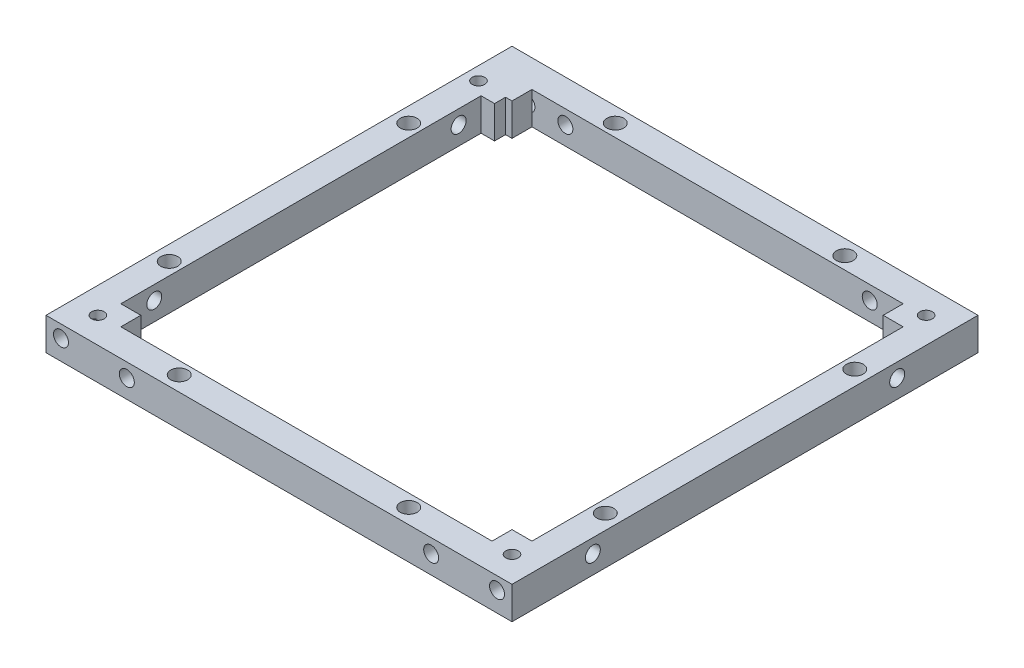
SolidWorks part; units mm, degrees
material "Aluminum"
ref_plane "Front Plane" through (0, 0, 0) normal (0, 0, 1) x (1, 0, 0)
ref_plane "Top Plane" through (0, 0, 0) normal (0, 1, 0) x (1, 0, 0)
ref_plane "Right Plane" through (0, 0, 0) normal (1, 0, 0) x (0, 0, -1)
sketch "Sketch1" plane through (0, 0, 0) normal (0, 1, 0) x (1, 0, 0)
  line L1 (46.7, -46.7) -> (-46.7, -46.7)
  line L2 (46.7, -46.7) -> (46.7, 46.7)
  line L3 (46.7, 46.7) -> (-46.7, 46.7)
  line L4 (-46.7, -46.7) -> (-46.7, 46.7)
  line L5 (46.7, -46.7) -> (-46.7, 46.7) construction
  line L6 (46.7, 46.7) -> (-46.7, -46.7) construction
  line L7 (38.7, -38.7) -> (-38.7, -38.7)
  line L8 (38.7, -38.7) -> (38.7, 38.7)
  line L9 (38.7, 38.7) -> (-38.7, 38.7)
  line L10 (-38.7, -38.7) -> (-38.7, 38.7)
  line L11 (38.7, -38.7) -> (-38.7, 38.7) construction
  line L12 (38.7, 38.7) -> (-38.7, -38.7) construction
  point P0 (0, 0)
  point P6 (0, 0)
  dimension "D1" = 93.4
  dimension "D2" = 93.4
  dimension "D3" = 8
extrude "Boss-Extrude1" add sketch "Sketch1" along normal blind 8
hole_wizard "Ø3.0 (3) Diameter Hole6" positions "Sketch8" profile "Sketch7" hole size "Ø3.0" standard "ANSI Metric"
sketch "Sketch8" plane through (0, 0, 46.7) normal (0, 0, 1) x (1, 0, 0)
  line L0 (46.7, 8) -> (46.7, 0) construction
  line L1 (-46.7, 8) -> (-46.7, 0) construction
  line L2 (-46.7, 0) -> (46.7, 0) construction
  point P0 (43.7, 4)
  point P2 (-43.7, 4)
  dimension "D1" = 3
  dimension "D2" = 3
  dimension "D3" = 4
  dimension "D4" = 4
sketch "Sketch7" plane through (43.7, 4, 46.7) normal (1, 0, 0) x (0, -1, 0)
  line L0 (0, 0) -> (0, 7.5)
  line L1 (0, 7.5) -> (1.5, 7.5)
  line L2 (1.5, 7.5) -> (1.5, 0)
  line L5 (1.5, 0) -> (0, 0)
  line L10 (0, 7.5) -> (-1.5, 7.5) construction
  line L11 (0, -6.35) -> (0, 107.95) construction
  dimension "Hole Dia." = 3
  dimension "Hole Depth" = 7.5
  dimension "Drill Angle" = 180
hole_wizard "Ø3.0 (3) Diameter Hole3" positions "Sketch10" profile "Sketch9" hole size "Ø3.0" standard "ANSI Metric"
sketch "Sketch10" plane through (0, 0, -46.7) normal (0, 0, -1) x (-1, 0, 0)
  line L0 (-46.7, 8) -> (-46.7, 0) construction
  line L1 (46.7, 8) -> (46.7, 0) construction
  line L2 (-46.7, 0) -> (46.7, 0) construction
  point P0 (-43.7, 4)
  point P2 (43.7, 4)
  dimension "D1" = 3
  dimension "D2" = 3
  dimension "D3" = 4
  dimension "D4" = 4
sketch "Sketch9" plane through (43.7, 4, -46.7) normal (1, 0, 0) x (0, 1, 0)
  line L0 (0, 0) -> (0, 7.5)
  line L1 (0, 7.5) -> (1.5, 7.5)
  line L2 (1.5, 7.5) -> (1.5, 0)
  line L5 (1.5, 0) -> (0, 0)
  line L10 (0, 7.5) -> (-1.5, 7.5) construction
  line L11 (0, -6.35) -> (0, 107.95) construction
  dimension "Hole Dia." = 3
  dimension "Hole Depth" = 7.5
  dimension "Drill Angle" = 180
sketch "Sketch27" plane through (0, 8, 0) normal (0, 1, 0) x (1, 0, 0)
  line L0 (-38.7, 38.7) -> (-38.7, -38.7) construction
  line L1 (39.7, -39.7) -> (-39.7, -39.7)
  line L2 (39.7, -39.7) -> (39.7, 39.7)
  line L3 (39.7, 39.7) -> (-39.7, 39.7)
  line L4 (-39.7, -39.7) -> (-39.7, 39.7)
  line L5 (39.7, -39.7) -> (-39.7, 39.7) construction
  line L6 (39.7, 39.7) -> (-39.7, -39.7) construction
  line L7 (38.7, 38.7) -> (-38.7, 38.7) construction
  point P0 (0, 0)
  dimension "D1" = 1
  dimension "D2" = 1
extrude "Cut-Extrude2" cut sketch "Sketch27" against normal blind 10
hole_wizard "Ø3.4 (3.4) Diameter Hole1" positions "Sketch37" profile "Sketch36" hole size "Ø3.4" standard "ANSI Metric" end condition through all
sketch "Sketch37" plane through (0, 0, 0) normal (0, -1, 0) x (-1, 0, 0)
  line L0 (39.7, -39.7) -> (-39.7, -39.7) construction
  line L1 (39.7, 39.7) -> (39.7, -39.7) construction
  line L2 (-39.7, -39.7) -> (-39.7, 39.7) construction
  line L3 (-39.7, 39.7) -> (39.7, 39.7) construction
  point P0 (-23, 43.7)
  point P2 (23, 43.7)
  point P4 (43.7, 23)
  point P6 (43.7, -25)
  point P8 (23, -43.7)
  point P10 (-23, -43.7)
  point P12 (-43.7, -25)
  point P14 (-43.7, 25)
  dimension "D1" = 46
  dimension "D2" = 4
  dimension "D3" = 48
  dimension "D4" = 50
  dimension "D5" = 46
  dimension "D6" = 4
  dimension "D7" = 4
  dimension "D8" = 4
sketch "Sketch36" plane through (23, 0, -43.7) normal (1, 0, 0) x (0, 0, -1)
  line L0 (0, 0) -> (0, 8)
  line L1 (0, 8) -> (1.7, 8)
  line L2 (1.7, 8) -> (1.7, 0)
  line L5 (1.7, 0) -> (0, 0)
  line L11 (0, -6.35) -> (0, 107.95) construction
  dimension "Thru Hole Dia." = 3.4
  dimension "Thru Hole Depth" = 8
sketch "Sketch38" plane through (0, 8, 0) normal (0, 1, 0) x (1, 0, 0)
  line L0 (46.7, 46.7) -> (-46.7, 46.7) construction
  line L1 (41.2, -41.2) -> (-41.2, -41.2)
  line L2 (41.2, -41.2) -> (41.2, 41.2)
  line L3 (41.2, 41.2) -> (-41.2, 41.2)
  line L4 (-41.2, -41.2) -> (-41.2, 41.2)
  line L5 (41.2, -41.2) -> (-41.2, 41.2) construction
  line L6 (41.2, 41.2) -> (-41.2, -41.2) construction
  line L7 (-46.7, 46.7) -> (-46.7, -46.7) construction
  point P0 (0, 0)
  dimension "D1" = 5.5
  dimension "D2" = 5.5
extrude "Cut-Extrude4" cut sketch "Sketch38" against normal blind 10
sketch "Sketch44" plane through (0, 0, 0) normal (0, -1, 0) x (1, 0, 0)
  line L0 (41.2, -41.2) -> (-41.2, -41.2) construction
  line L1 (41.2, -41.2) -> (37.2, -41.2)
  line L2 (41.2, -41.2) -> (41.2, -37.2)
  line L3 (41.2, -37.2) -> (37.2, -37.2)
  line L4 (37.2, -41.2) -> (37.2, -37.2)
  line L5 (41.2, 41.2) -> (41.2, -41.2) construction
  line L6 (0, 0) -> (0, -67.1068) construction
  line L7 (0, 0) -> (66.4168, 0) construction
  line L8 (-37.2, -41.2) -> (-37.2, -37.2)
  line L9 (-41.2, -37.2) -> (-37.2, -37.2)
  line L10 (-41.2, -41.2) -> (-41.2, -37.2)
  line L11 (-41.2, -41.2) -> (-37.2, -41.2)
  line L12 (-41.2, 41.2) -> (-37.2, 41.2)
  line L13 (-41.2, 41.2) -> (-41.2, 37.2)
  line L14 (-41.2, 37.2) -> (-37.2, 37.2)
  line L15 (-37.2, 41.2) -> (-37.2, 37.2)
  line L16 (37.2, 41.2) -> (37.2, 37.2)
  line L17 (41.2, 37.2) -> (37.2, 37.2)
  line L18 (41.2, 41.2) -> (41.2, 37.2)
  line L19 (41.2, 41.2) -> (37.2, 41.2)
  dimension "D1" = 4
  dimension "D2" = 4
extrude "Boss-Extrude2" add sketch "Sketch44" against normal blind 8
sketch "Sketch45" plane through (0, 8, 0) normal (0, 1, 0) x (1, 0, 0)
  line L1 (-42.5, 38.5) -> (-38.5, 38.5)
  line L2 (-42.5, 38.5) -> (-42.5, 35)
  line L3 (-42.5, 35) -> (-38.5, 35)
  line L4 (-38.5, 38.5) -> (-38.5, 35)
  dimension "D1" = 4
  dimension "D2" = 3.5
extrude "Boss-Extrude3" add sketch "Sketch45" against normal blind 8
hole_wizard "Tap Drill for M3x0.5 Tap1" positions "Sketch48" profile "Sketch46" hole size "M3x0.5" standard "ANSI Metric" end condition through all
sketch "Sketch48" plane through (0, 8, 0) normal (0, 1, 0) x (1, 0, 0)
  point P0 (41.5, 41.5)
  point P2 (41.5, -41.5)
  point P4 (-41.5, -41.5)
  point P6 (-44.05, 37.33)
sketch "Sketch46" plane through (41.5, 8, -41.5) normal (1, 0, 0) x (0, 0, 1)
  line L0 (0, 0) -> (0, 8)
  line L1 (0, 8) -> (1.25, 8)
  line L2 (1.25, 8) -> (1.25, 0)
  line L5 (1.25, 0) -> (0, 0)
  line L11 (0, -6.35) -> (0, 107.95) construction
  dimension "Thru Hole Dia." = 2.5
  dimension "Thru Hole Depth" = 8
sketch "Sketch49" plane through (46.7, 0, 0) normal (1, 0, 0) x (0, 0, -1)
  line L0 (46.7, 8) -> (46.7, 0) construction
  line L1 (-46.7, 8) -> (46.7, 8)
  line L2 (-46.7, 8) -> (-46.7, 6.5)
  line L3 (-46.7, 6.5) -> (46.7, 6.5)
  line L4 (46.7, 8) -> (46.7, 6.5)
  dimension "D1" = 1.5
extrude "Cut-Extrude5" cut sketch "Sketch49" against normal blind 146
hole_wizard "Tap Drill for M3x0.5 Tap2" positions "Sketch51" profile "Sketch50" hole size "M3x0.5" standard "ANSI Metric"
sketch "Sketch51" plane through (-46.7, 0, 0) normal (-1, 0, 0) x (0, 0, 1)
  point P0 (30.5, 3.7)
  point P3 (-30.5, 3.7)
sketch "Sketch50" plane through (-46.7, 3.7, 30.5) normal (0, 1, 0) x (0, 0, 1)
  line L0 (0, 0) -> (0, 5.5)
  line L1 (0, 5.5) -> (1.5, 5.5)
  line L2 (1.5, 5.5) -> (1.5, 0)
  line L5 (1.5, 0) -> (0, 0)
  line L11 (0, -6.35) -> (0, 107.95) construction
  dimension "Thru Hole Dia." = 3
  dimension "Thru Hole Depth" = 5.5
hole_wizard "Tap Drill for M3x0.5 Tap3" positions "Sketch53" profile "Sketch52" hole size "M3x0.5" standard "ANSI Metric"
sketch "Sketch53" plane through (0, 0, -46.7) normal (0, 0, -1) x (-1, 0, 0)
  point P0 (30.5, 3.7)
  point P3 (-30.5, 3.7)
sketch "Sketch52" plane through (-30.5, 3.7, -46.7) normal (1, 0, 0) x (0, 1, 0)
  line L0 (0, 0) -> (0, 5.5)
  line L1 (0, 5.5) -> (1.5, 5.5)
  line L2 (1.5, 5.5) -> (1.5, 0)
  line L5 (1.5, 0) -> (0, 0)
  line L11 (0, -6.35) -> (0, 107.95) construction
  dimension "Thru Hole Dia." = 3
  dimension "Thru Hole Depth" = 5.5
hole_wizard "Tap Drill for M3x0.5 Tap4" positions "Sketch55" profile "Sketch54" hole size "M3x0.5" standard "ANSI Metric" end condition up to next
sketch "Sketch55" plane through (46.7, 0, 0) normal (1, 0, 0) x (0, 0, -1)
  point P0 (30.5, 3.7)
  point P3 (-30.5, 3.7)
sketch "Sketch54" plane through (46.7, 3.7, -30.5) normal (0, 1, 0) x (0, 0, -1)
  line L0 (0, 0) -> (0, 5.5)
  line L1 (0, 5.5) -> (1.5, 5.5)
  line L2 (1.5, 5.5) -> (1.5, 0)
  line L5 (1.5, 0) -> (0, 0)
  line L11 (0, -6.35) -> (0, 107.95) construction
  dimension "Thru Hole Dia." = 3
  dimension "Thru Hole Depth" = 5.5
hole_wizard "Tap Drill for M3x0.5 Tap5" positions "Sketch57" profile "Sketch56" hole size "M3x0.5" standard "ANSI Metric" end condition up to next
sketch "Sketch57" plane through (0, 0, 46.7) normal (0, 0, 1) x (1, 0, 0)
  point P0 (30.5, 3.7)
  point P3 (-30.5, 3.7)
sketch "Sketch56" plane through (30.5, 3.7, 46.7) normal (1, 0, 0) x (0, -1, 0)
  line L0 (0, 0) -> (0, 5.5)
  line L1 (0, 5.5) -> (1.5, 5.5)
  line L2 (1.5, 5.5) -> (1.5, 0)
  line L5 (1.5, 0) -> (0, 0)
  line L11 (0, -6.35) -> (0, 107.95) construction
  dimension "Thru Hole Dia." = 3
  dimension "Thru Hole Depth" = 5.5
hole_wizard "Tap Drill for M3x0.5 Tap6" positions "Sketch59" profile "Sketch58" hole size "M3x0.5" standard "ANSI Metric"
sketch "Sketch59" plane through (0, 0, -46.7) normal (0, 0, -1) x (-1, 0, 0)
  line L0 (0, 0) -> (0, -19.6512) construction
  point P0 (38.1, 3.7)
  point P2 (-38.1, 3.7)
  dimension "D1" = 38.1
  dimension "D2" = 38.1
sketch "Sketch58" plane through (-38.1, 3.7, -46.7) normal (1, 0, 0) x (0, 1, 0)
  line L0 (0, 0) -> (0, 5.5)
  line L1 (0, 5.5) -> (1.5, 5.5)
  line L2 (1.5, 5.5) -> (1.5, 0)
  line L5 (1.5, 0) -> (0, 0)
  line L10 (0, 5.5) -> (-1.5, 5.5) construction
  line L11 (0, -6.35) -> (0, 107.95) construction
  dimension "Hole Dia." = 3
  dimension "Hole Depth" = 5.5
  dimension "Drill Angle" = 180
